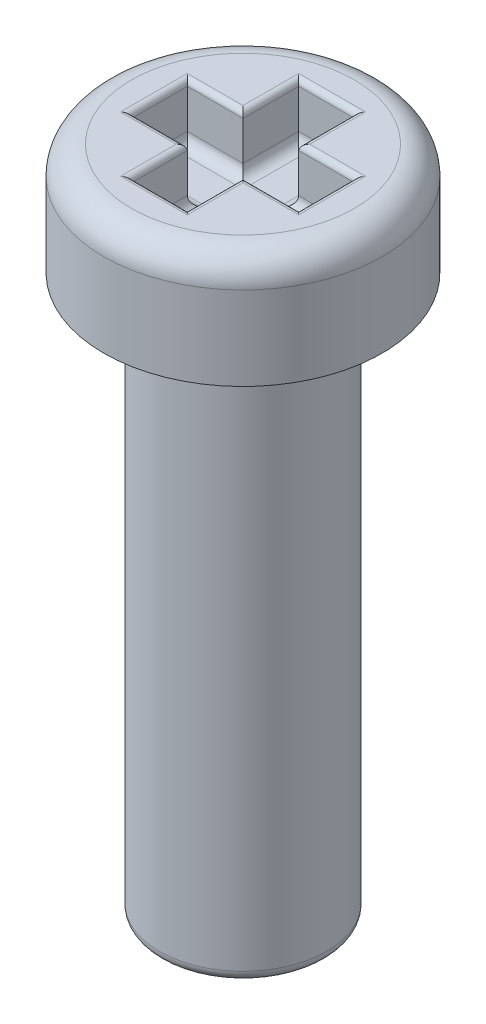
SolidWorks part; units mm, degrees
ref_plane "Front Plane" through (0, 0, 0) normal (0, 0, 1) x (1, 0, 0)
ref_plane "Top Plane" through (0, 0, 0) normal (0, 1, 0) x (1, 0, 0)
ref_plane "Right Plane" through (0, 0, 0) normal (1, 0, 0) x (0, 0, -1)
sketch "Sketch1" plane through (0, 0, 0) normal (0, 1, 0) x (1, 0, 0)
  circle A0 centre (0, 0) radius 1.5
  dimension "D1" = 3
extrude "Boss-Extrude1" add sketch "Sketch1" along normal blind 10
fillet "Fillet1" radius 0.2 1 edges at (0, 0, 1.5)
sketch "Sketch2" plane through (0, 0, 0) normal (0, 0, 1) x (1, 0, 0)
  line L0 (0, 0) -> (0, 13.199) construction
  line L1 (0, 10) -> (-2.5, 10)
  line L2 (1.5, 10) -> (-1.5, 10) construction
  line L3 (-2.5, 10) -> (-2.5, 12)
  line L4 (-2.5, 12) -> (0, 12)
  line L5 (0, 12) -> (0, 10)
  dimension "D1" = 2
  dimension "D2" = 2.5
revolve "Revolve1" add sketch "Sketch2" angle 360 about L0
sketch "Sketch3" plane through (0, 12, 0) normal (0, 1, 0) x (1, 0, 0)
  line L0 (0, -1003) -> (0, -1.5) construction
  line L1 (-1003, 0) -> (-1.5, 0) construction
  line L2 (-0.5, 0.5) -> (-1.5, 0.5)
  line L3 (-0.5, 1.5) -> (0.5, 1.5)
  line L4 (-0.5, 1.5) -> (-0.5, 0.5)
  line L5 (-0.5, -1.5) -> (0.5, -1.5)
  line L6 (0.5, 1.5) -> (0.5, 0.5)
  line L7 (0, -0.5) -> (0, 1.5) construction
  line L8 (-0.5, 0) -> (0.5, 0) construction
  line L9 (1.5, 0.5) -> (0.5, 0.5)
  line L10 (1.5, 0.5) -> (1.5, -0.5)
  line L11 (1.5, -0.5) -> (0.5, -0.5)
  line L12 (-1.5, 0.5) -> (-1.5, -0.5)
  line L13 (0, -0.5) -> (0, 0.5) construction
  line L14 (0.5, 0) -> (-0.5, 0) construction
  line L15 (-0.5, -0.5) -> (-0.5, -1.5)
  line L16 (-0.5, 0) -> (0.5, 0) construction
  line L17 (-0.5, -0.5) -> (-1.5, -0.5)
  line L18 (0, -0.5) -> (0, 50000) construction
  line L19 (0.5, -0.5) -> (0.5, -1.5)
  line L20 (1.5, 0) -> (50000, 0) construction
  point P5 (0, 0)
  point P9 (0, 0)
  dimension "D1" = 1
  dimension "D2" = 1
  dimension "D3" = 1
  dimension "D4" = 1
extrude "Cut-Extrude1" cut sketch "Sketch3" against normal blind 1
fillet "Fillet3" radius 0.1 12 edges at (-1, 12, 0.5) (-0.5, 12, 1) (0, 12, 1.5) (0.5, 12, 1) (1, 12, 0.5) (1.5, 12, 0) (1, 12, -0.5) (0.5, 12, -1) (0, 12, -1.5) (-0.5, 12, -1) (-1, 12, -0.5) (-1.5, 12, 0)
fillet "Fillet4" radius 0.2 12 edges at (-1, 11, -0.5) (-1.5, 11, 0) (-1, 11, 0.5) (-0.5, 11, 1) (0.5, 11, 1) (0, 11, 1.5) (1, 11, 0.5) (1.5, 11, 0) (1, 11, -0.5) (0.5, 11, -1) (0, 11, -1.5) (-0.5, 11, -1)
fillet "Fillet5" radius 0.5 1 edges at (0, 12, -2.5)
